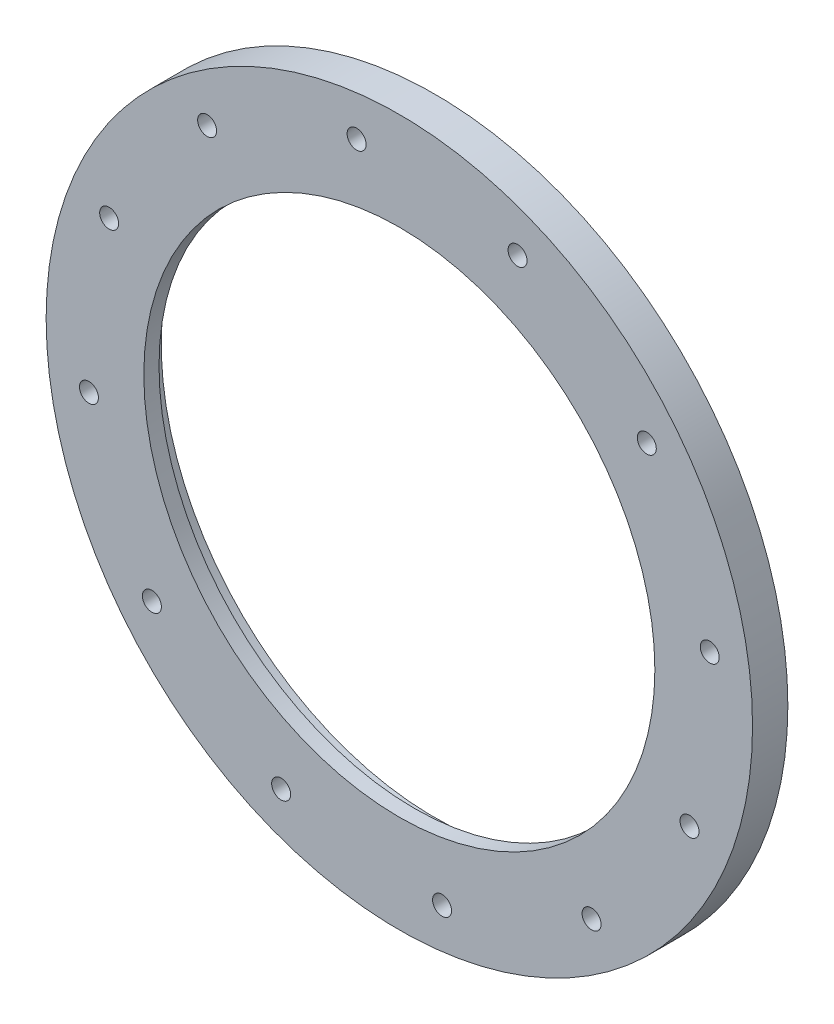
SolidWorks part; units mm, degrees
ref_plane "Front Plane" through (0, 0, 0) normal (0, 0, 1) x (1, 0, 0)
ref_plane "Top Plane" through (0, 0, 0) normal (0, 1, 0) x (1, 0, 0)
ref_plane "Right Plane" through (0, 0, 0) normal (1, 0, 0) x (0, 0, -1)
sketch "Sketch1" plane through (0, 0, 0) normal (0, 0, 1) x (1, 0, 0)
  circle A0 centre (0, 0) radius 46.5
  circle A1 centre (0, 0) radius 36
  dimension "D1" = 93
  dimension "D2" = 72
extrude "Boss-Extrude1" add sketch "Sketch1" along normal mid plane 4.65
sketch "Sketch2" plane through (0, 0, 2.325) normal (0, 0, 1) x (1, 0, 0)
  circle A0 centre (0, 0) radius 33.6389
  circle A1 centre (0, 0) radius 36 construction
  circle A2 centre (0, 0) radius 36
  dimension "D1" = 67.2778
extrude "Boss-Extrude2" add sketch "Sketch2" against normal blind 2
sketch "Sketch3" plane through (0, 0, 2.325) normal (0, 0, 1) x (1, 0, 0)
  circle A0 centre (-15.5601, -38.2027) radius 1.25 construction
  circle A1 centre (-32.5768, -25.3044) radius 1.25 construction
  circle A2 centre (-40.8646, -5.6259) radius 1.25 construction
  circle A3 centre (-38.2027, 15.5601) radius 1.25 construction
  circle A4 centre (-25.3044, 32.5768) radius 1.25 construction
  circle A5 centre (-5.6259, 40.8646) radius 1.25 construction
  circle A6 centre (15.5601, 38.2027) radius 1.25 construction
  circle A7 centre (32.5768, 25.3044) radius 1.25 construction
  circle A8 centre (40.8646, 5.6259) radius 1.25 construction
  circle A9 centre (38.2027, -15.5601) radius 1.25 construction
  circle A10 centre (25.3044, -32.5768) radius 1.25 construction
  circle A11 centre (5.6259, -40.8646) radius 1.25 construction
  circle A12 centre (-15.5601, -38.2027) radius 1.25
  circle A13 centre (-32.5768, -25.3044) radius 1.25
  circle A14 centre (-40.8646, -5.6259) radius 1.25
  circle A15 centre (-38.2027, 15.5601) radius 1.25
  circle A16 centre (-25.3044, 32.5768) radius 1.25
  circle A17 centre (-5.6259, 40.8646) radius 1.25
  circle A18 centre (15.5601, 38.2027) radius 1.25
  circle A19 centre (32.5768, 25.3044) radius 1.25
  circle A20 centre (40.8646, 5.6259) radius 1.25
  circle A21 centre (38.2027, -15.5601) radius 1.25
  circle A22 centre (25.3044, -32.5768) radius 1.25
  circle A23 centre (5.6259, -40.8646) radius 1.25
extrude "Cut-Extrude1" cut sketch "Sketch3" against normal through all both and the other way through all
